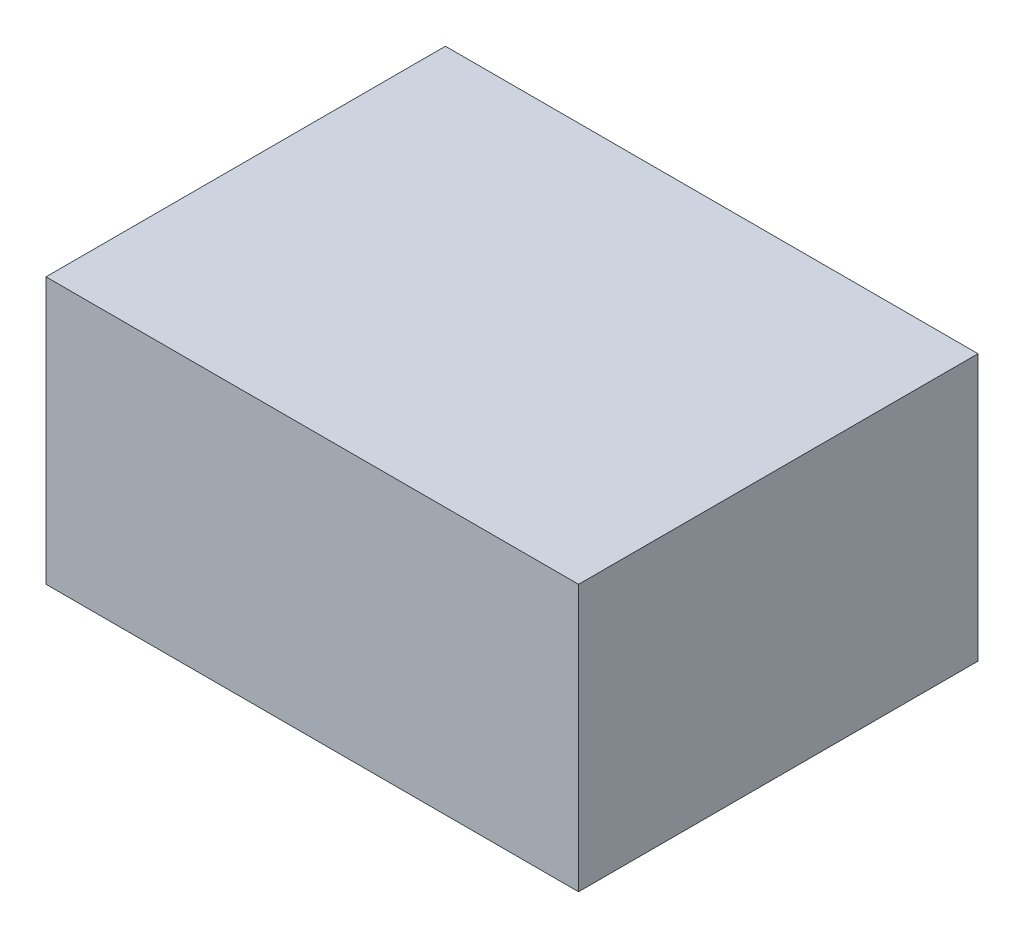
SolidWorks part; units mm, degrees
ref_plane "Front Plane" through (0, 0, 0) normal (0, 0, 1) x (1, 0, 0)
ref_plane "Top Plane" through (0, 0, 0) normal (0, 1, 0) x (1, 0, 0)
ref_plane "Right Plane" through (0, 0, 0) normal (1, 0, 0) x (0, 0, -1)
sketch "Sketch1" plane through (0, 0, 0) normal (0, 1, 0) x (1, 0, 0)
  line L1 (-60, 45) -> (0, 45)
  line L2 (-60, 45) -> (-60, 0)
  line L3 (-60, 0) -> (0, 0)
  line L4 (0, 45) -> (0, 0)
  dimension "D1" = 60
  dimension "D2" = 45
extrude "Boss-Extrude1" add sketch "Sketch1" along normal blind 30
sketch "Sketch2" plane through (0, 0, 0) normal (0, -1, 0) x (-1, 0, 0)
  line L1 (51, 13) -> (43, 13)
  line L2 (51, 13) -> (51, 29)
  line L3 (51, 29) -> (43, 29)
  line L4 (43, 13) -> (43, 29)
  line L5 (17, 13) -> (9, 13)
  line L6 (17, 13) -> (17, 29)
  line L7 (17, 29) -> (9, 29)
  line L8 (9, 13) -> (9, 29)
  line L9 (11, 43.15) -> (28.1984, 43.15) construction
  line L10 (0, 0) -> (0, 45) construction
  line L11 (11, 43.15) -> (11, 34.15) construction
  line L12 (0, 45) -> (60, 45) construction
  line L13 (11, 34.15) -> (28.1984, 34.15) construction
  line L14 (28.1984, 43.15) -> (28.1984, 34.15) construction
  dimension "D1" = 16
  dimension "D2" = 8
  dimension "D3" = 26
  dimension "D4" = 8
  dimension "D5" = 16
  dimension "D6" = 9
  dimension "D7" = 16
  dimension "D8" = 2
  dimension "D9" = 9
  dimension "D10" = 5.15
  dimension "D11" = 17.1984
extrude "Cut-Extrude1" cut sketch "Sketch2" against normal blind 20
chamfer "Chamfer1" distance 15 angle 5 4 edges at (-17, 20, -21) (-9, 20, -21) (-51, 20, -21) (-43, 20, -21)
chamfer "Chamfer2" distance 5 angle 50 4 edges at (-47, 20, -29) (-13, 20, -29) (-13, 20, -13) (-47, 20, -13)
sketch "Sketch4" plane through (0, 0, -45) normal (0, 0, -1) x (-1, 0, 0)
  line L0 (10, 0) -> (28.5, 0)
  line L1 (0, 0) -> (60, 0) construction
  arc A0 (28.5, 0) -> (42.3979, 6.3136) centre (38.3836, -3.3031) cw
  arc A1 (42.3979, 6.3136) -> (45.7403, 11.7612) centre (43.6438, 9.2984) ccw
  arc A2 (45.7403, 11.7612) -> (10, 0) centre (31.4568, -5.0184) ccw
  dimension "D1" = 18.5
  dimension "D2" = 10
extrude "Cut-Extrude2" cut sketch "Sketch4" against normal blind 10
